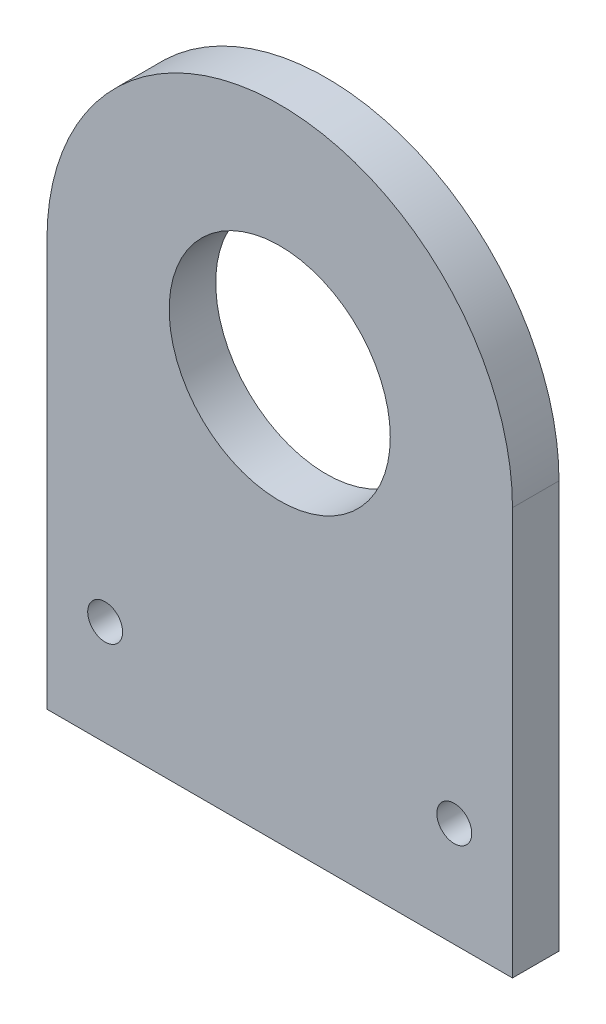
SolidWorks part; units mm, degrees
material "Thornel Mat VMA"
ref_plane "前视基准面" through (0, 0, 0) normal (0, 0, 1) x (1, 0, 0)
ref_plane "上视基准面" through (0, 0, 0) normal (0, 1, 0) x (1, 0, 0)
ref_plane "右视基准面" through (0, 0, 0) normal (1, 0, 0) x (0, 0, -1)
sketch "草图1" plane through (0, 0, 0) normal (0, 0, 1) x (1, 0, 0)
  line L0 (-20, 0) -> (-20, -35)
  line L1 (-20, -35) -> (20, -35)
  line L2 (20, -35) -> (20, 0)
  circle A0 centre (0, 0) radius 20
  dimension "D1" = 40
  dimension "D2" = 35
extrude "凸台-拉伸1" add sketch "草图1" along normal blind 4 contours A0 | A0 L0 L1 L2
sketch "草图2" plane through (0, 0, 4) normal (0, 0, 1) x (1, 0, 0)
  circle A0 centre (0, 0) radius 9.5
  dimension "D1" = 19
extrude "切除-拉伸1" cut sketch "草图2" against normal through all
sketch "草图4" plane through (0, 0, 4) normal (0, 0, 1) x (1, 0, 0)
  line L0 (-20, -26) -> (20, -26) construction
  line L1 (-20, 0) -> (-20, -35) construction
  line L2 (20, -35) -> (20, 0) construction
  line L3 (-20, -35) -> (20, -35) construction
  line L4 (0, -26) -> (0, -35) construction
  circle A0 centre (-15, -26) radius 1.5
  circle A1 centre (15, -26) radius 1.5
  dimension "D2" = 15
  dimension "D3" = 3
  dimension "D1" = 9
extrude "切除-拉伸2" cut sketch "草图4" against normal through all
